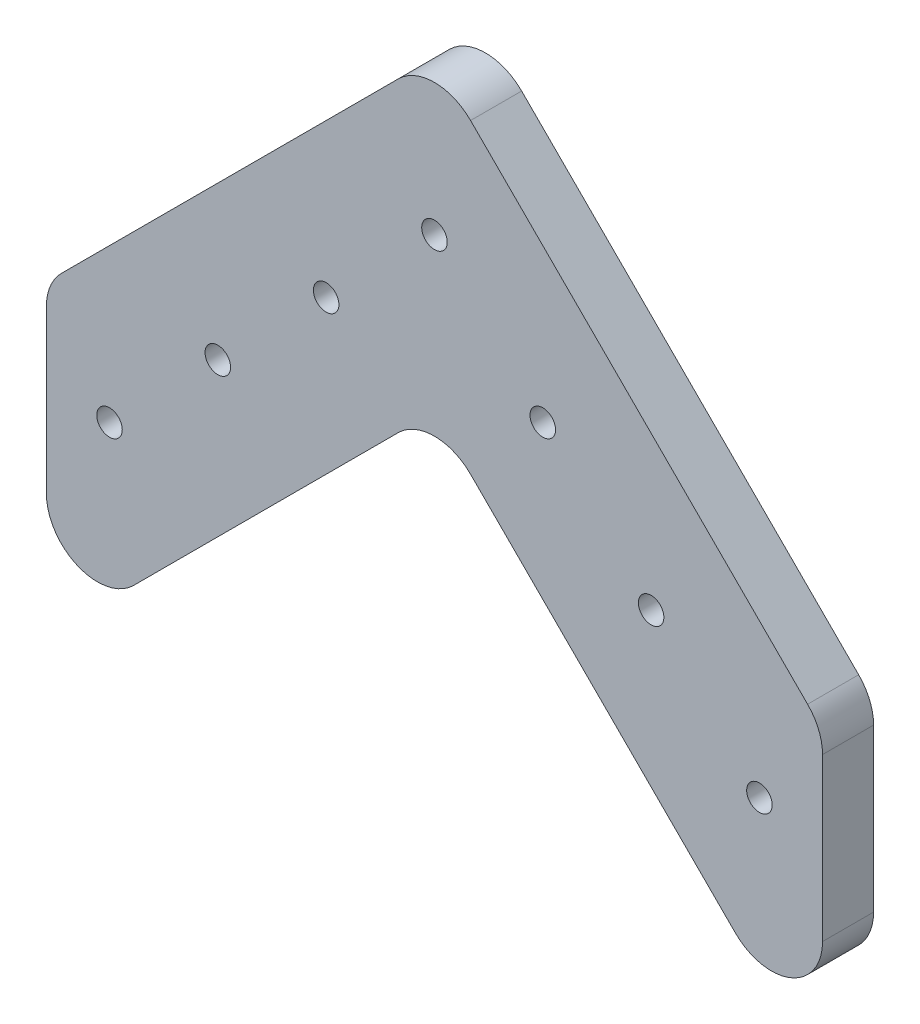
SolidWorks part; units mm, degrees
ref_plane "Front Plane" through (0, 0, 0) normal (0, 0, 1) x (1, 0, 0)
ref_plane "Top Plane" through (0, 0, 0) normal (0, 1, 0) x (1, 0, 0)
ref_plane "Right Plane" through (0, 0, 0) normal (1, 0, 0) x (0, 0, -1)
sketch "Sketch1" plane through (0, 0, 0) normal (0, 0, 1) x (1, 0, 0)
  line L0 (0, 110) -> (0, 0) construction
  line L1 (-40, 0) -> (-40, 70) construction
  line L2 (-40, 70) -> (0, 110) construction
  line L3 (0, 0) -> (-40, 0) construction
  line L4 (-38, 74.8284) -> (0, 112.8284)
  line L5 (-38, 74.8284) -> (-38, 104.8284)
  line L6 (-38, 104.8284) -> (0, 142.8284)
  line L7 (-38, 89.8284) -> (0, 127.8284) construction
  line L8 (0, 112.8284) -> (0, 142.8284) construction
  line L9 (38, 104.8284) -> (0, 142.8284)
  line L10 (38, 74.8284) -> (0, 112.8284)
  line L11 (38, 74.8284) -> (38, 104.8284)
  circle A0 centre (-31.8198, 96.0086) radius 1.25
  circle A1 centre (-21.2132, 106.6152) radius 1.25
  circle A2 centre (-10.6066, 117.2218) radius 1.25
  circle A3 centre (0, 127.8284) radius 1.25
  circle A4 centre (10.6066, 117.2218) radius 1.25
  circle A5 centre (21.2132, 106.6152) radius 1.25
  circle A6 centre (31.8198, 96.0086) radius 1.25
  point P18 (0, 0)
  point P19 (0, 122.6515)
  point P20 (0, 0)
  point P21 (0, 127.8284)
  dimension "D7" = 2.5
  dimension "D1" = 70
  dimension "D2" = 40
  dimension "D3" = 40
  dimension "D4" = 4
  dimension "D5" = 2
  dimension "D6" = 30
  dimension "D8" = 15
  dimension "D9" = 15
  dimension "D10" = 15
extrude "Boss-Extrude1" add sketch "Sketch1" along normal blind 5
fillet "Fillet1" radius 5 6 edges at (0, 112.8284, 2.5) (-38, 74.8284, 2.5) (38, 74.8284, 2.5) (38, 104.8284, 2.5) (0, 142.8284, 2.5) (-38, 104.8284, 2.5)
